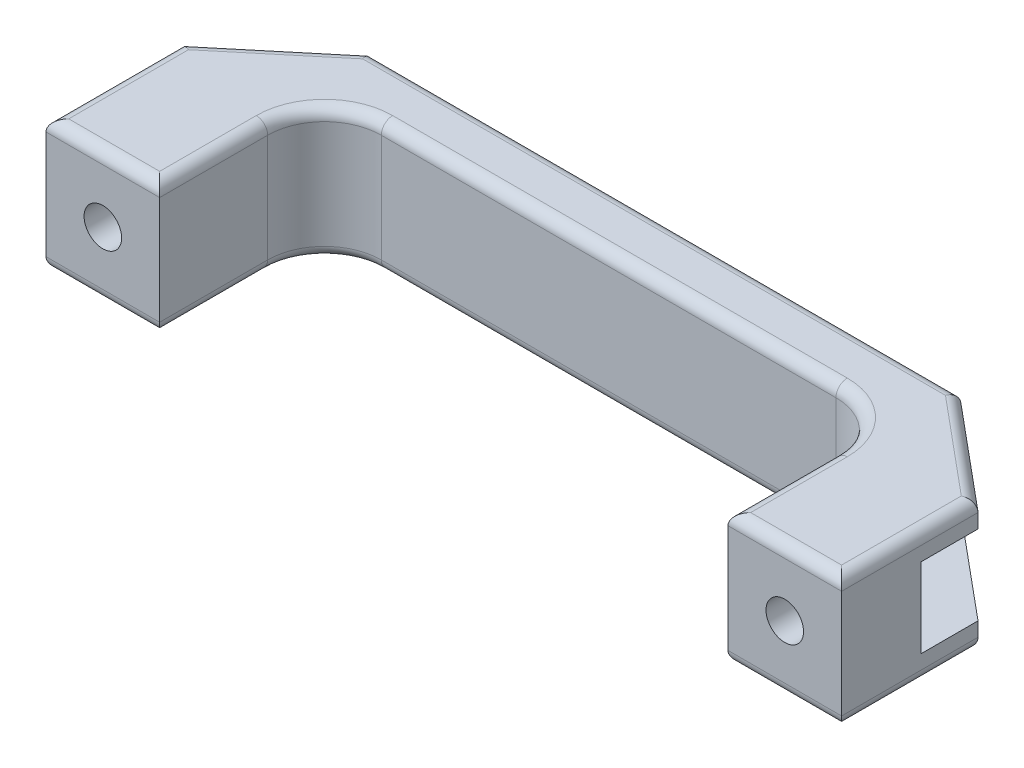
SolidWorks part; units mm, degrees
material "6061 合金"
ref_plane "前视基准面" through (0, 0, 0) normal (0, 0, 1) x (1, 0, 0)
ref_plane "上视基准面" through (0, 0, 0) normal (0, 1, 0) x (1, 0, 0)
ref_plane "右视基准面" through (0, 0, 0) normal (1, 0, 0) x (0, 0, -1)
other "Configuration Table"
sketch "草图1" plane through (0, 0, 0) normal (0, 1, 0) x (1, 0, 0)
  line L0 (-50, 0) -> (-50, 29)
  line L1 (-50, 29) -> (50, 29)
  line L2 (50, 29) -> (50, 0)
  line L3 (50, 0) -> (70, 0)
  line L4 (70, 0) -> (70, 24)
  line L5 (70, 24) -> (52, 39)
  line L6 (52, 39) -> (-52, 39)
  line L7 (-52, 39) -> (-70, 24)
  line L8 (-70, 24) -> (-70, 0)
  line L9 (-70, 0) -> (-50, 0)
  line L10 (0, 29) -> (0, 0) construction
  point P17 (0, 39)
  dimension "D1" = 140
  dimension "D2" = 39
  dimension "D3" = 20
  dimension "D4" = 10
  dimension "D5" = 24
  dimension "D6" = 104
extrude "凸台-拉伸1" add sketch "草图1" along normal blind 23
sketch "草图2" plane through (0, 0, 0) normal (0, 0, 1) x (1, 0, 0)
  line L0 (0, 23) -> (0, 0) construction
  line L1 (-50, 23) -> (50, 23) construction
  line L2 (-50, 23) -> (-50, 0) construction
  circle A0 centre (-60, 11.5) radius 3.25
  circle A1 centre (60, 11.5) radius 3.25
  point P11 (-50, 11.5)
  dimension "D1" = 60
  dimension "8.5" = 6.5
extrude "切除-拉伸1" cut sketch "草图2" against normal through all both and the other way through all
sketch "草图3" plane through (0, 0, 0) normal (0, 0, 1) x (1, 0, 0)
  line L0 (50, 11.5) -> (52.5, 11.5) construction
  line L1 (85.1035, 18.5) -> (52.5, 18.5)
  line L2 (85.1035, 18.5) -> (85.1035, 4.5)
  line L3 (85.1035, 4.5) -> (52.5, 4.5)
  line L4 (52.5, 18.5) -> (52.5, 4.5)
  line L5 (50, 23) -> (50, 0) construction
  line L6 (50, 23) -> (50, 0) construction
  line L7 (0, 0) -> (0, 23) construction
  line L8 (-50, 23) -> (50, 23) construction
  line L9 (-50, 11.5) -> (-52.5, 11.5) construction
  line L10 (-52.5, 18.5) -> (-52.5, 4.5)
  line L11 (-85.1035, 4.5) -> (-52.5, 4.5)
  line L12 (-85.1035, 18.5) -> (-85.1035, 4.5)
  line L13 (-85.1035, 18.5) -> (-52.5, 18.5)
  dimension "D1" = 2.5
  dimension "D2" = 14
extrude "切除-拉伸2" cut sketch "草图3" against normal through all from offset 14 offset against normal yes
fillet "圆角1" radius 10 2 edges at (50, 11.5, -29) (-50, 11.5, -29)
hole_wizard "M6 六角凹锥坑螺钉的锥形沉头孔1" positions "3D草图1" profile "草图5" countersink size "M6" standard "ISO" end condition through all
sketch3d "3D草图1"
  line L0 (60, 11.5, -14) -> (60, 11.5, 0) construction
  line L1 (-60, 11.5, -14) -> (-60, 11.5, 0) construction
  point P0 (60, 11.5, -14)
  point P4 (-60, 11.5, -14)
sketch "草图5" plane through (60, 11.5, -14) normal (1, 0, 0) x (0, 1, 0)
  line L0 (0, 0) -> (0, 14)
  line L1 (0, 14) -> (3.3, 14)
  line L2 (3.3, 14) -> (3.3, 3.42)
  line L3 (3.3, 3.42) -> (6.72, 0)
  line L5 (6.72, 0) -> (0, 0)
  line L6 (-3.3, 3.42) -> (-6.72, 0) construction
  line L11 (0, -6.35) -> (0, 107.95) construction
  dimension "通孔孔直径" = 6.6
  dimension "通孔孔深度" = 14
  dimension "近端锥形沉头孔直径" = 13.44
  dimension "近端锥形沉头孔角度" = 90
fillet "圆角2" radius 2 26 edges at (-50, 0, -9.5) (-47.0711, 0, -26.0711) (0, 0, -29) (47.0711, 0, -26.0711) (50, 0, -9.5) (60, 0, 0) (70, 0, -12) (61, 0, -31.5) (0, 0, -39) (-61, 0, -31.5) (-70, 0, -12) (-60, 0, 0) (-70, 23, -12) (-61, 23, -31.5) (0, 23, -39) (61, 23, -31.5) (70, 23, -12) (60, 23, 0) (50, 23, -9.5) (47.0711, 23, -26.0711) (0, 23, -29) (-47.0711, 23, -26.0711) (-50, 23, -9.5) (-60, 23, 0) (-52.5, 4.5, -26.2917) (-52.5, 18.5, -26.2917)
